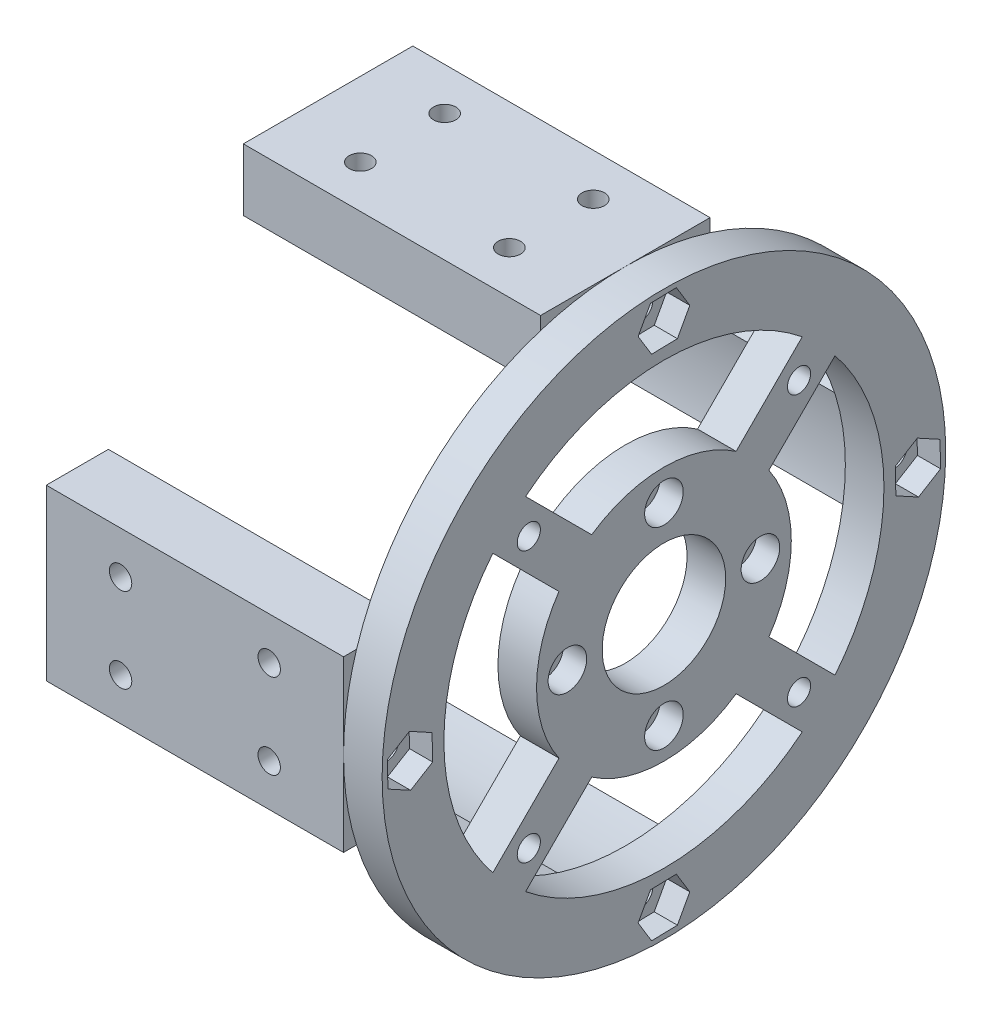
SolidWorks part; units mm, degrees
material "聚脂树脂"
ref_plane "前视基准面" through (0, 0, 0) normal (0, 0, 1) x (1, 0, 0)
ref_plane "上视基准面" through (0, 0, 0) normal (0, 1, 0) x (1, 0, 0)
ref_plane "右视基准面" through (0, 0, 0) normal (1, 0, 0) x (0, 0, -1)
sketch "草图1" plane through (0, 0, 0) normal (1, 0, 0) x (0, 0, -1)
  line L2 (13.5941, 9.3515) -> (22.1619, 17.9193)
  line L3 (9.3515, 13.5941) -> (17.9193, 22.1619)
  line L4 (13.5941, -9.3515) -> (22.1619, -17.9193)
  line L5 (9.3515, -13.5941) -> (17.9193, -22.1619)
  line L6 (-9.3515, -13.5941) -> (-17.9193, -22.1619)
  line L7 (-13.5941, -9.3515) -> (-22.1619, -17.9193)
  line L8 (-13.5941, 9.3515) -> (-22.1619, 17.9193)
  line L9 (-9.3515, 13.5941) -> (-17.9193, 22.1619)
  circle A0 centre (0, 0) radius 36.5
  circle A2 centre (0, 12.5) radius 1.55
  circle A3 centre (12.5, 0) radius 1.55
  circle A4 centre (0, -12.5) radius 1.55
  circle A5 centre (-12.5, 0) radius 1.55
  circle A6 centre (0, 0) radius 8
  arc A7 (17.9193, 22.1619) -> (-17.9193, 22.1619) centre (0, 0) ccw
  arc A8 (9.3515, 13.5941) -> (-9.3515, 13.5941) centre (0, 0) ccw
  arc A9 (-13.5941, 9.3515) -> (-13.5941, -9.3515) centre (0, 0) ccw
  arc A10 (-9.3515, -13.5941) -> (9.3515, -13.5941) centre (0, 0) ccw
  arc A14 (13.5941, -9.3515) -> (13.5941, 9.3515) centre (0, 0) ccw
  arc A15 (-22.1619, 17.9193) -> (-22.1619, -17.9193) centre (0, 0) ccw
  arc A16 (-17.9193, -22.1619) -> (17.9193, -22.1619) centre (0, 0) ccw
  arc A17 (22.1619, -17.9193) -> (22.1619, 17.9193) centre (0, 0) ccw
  point P15 (0, 0)
  point P37 (0, 0)
  dimension "73" = 73
  dimension "D3" = 3.1
  dimension "D5" = 16
  dimension "D6" = 57
  dimension "D7" = 33
  dimension "D4" = 4
  dimension "D11" = 4
extrude "凸台-拉伸1" add sketch "草图1" against normal blind 5
sketch "草图2" plane through (-5, 0, 0) normal (-1, 0, 0) x (0, 0, 1)
  line L0 (0, 30.5) -> (0, 36.5)
  line L1 (5.9179, 29.9204) -> (7.0821, 35.8063)
  line L2 (-7.0821, 35.8063) -> (-5.9179, 29.9204)
  line L3 (29.9025, -6.0076) -> (35.7885, -7.1718)
  line L4 (35.7885, 6.9924) -> (29.9025, 5.8282)
  line L5 (-6.0255, -29.9922) -> (-7.1896, -35.8781)
  line L6 (6.9745, -35.8781) -> (5.8104, -29.9922)
  line L7 (-30.01, 5.9358) -> (-35.896, 7.1)
  line L8 (-35.896, -7.0642) -> (-30.01, -5.9)
  circle A0 centre (0, 0) radius 30.5
  circle A1 centre (0, 0) radius 36.5 construction
  circle A2 centre (0, 0) radius 36.5
  point P12 (6.5, 32.8634)
  point P13 (0, 33.5)
  point P14 (-6.5, 32.8634)
  point P30 (-0.0538, -0.0359)
  dimension "D1" = 61
  dimension "D2" = 6.5
  dimension "D3" = 6.5
  dimension "D4" = 4
sketch "草图3" plane through (0, 0, 0) normal (1, 0, 0) x (0, 0, -1)
  circle A2 centre (2.4306, -32.8101) radius 1.55
  circle A3 centre (35.9279, -71.3329) radius 1.55
  circle A4 centre (-2.5949, -104.8302) radius 1.55
  circle A5 centre (-36.0922, -66.3074) radius 1.55
  circle A6 centre (0, 0) radius 32.9
  point P16 (-0.0822, -68.8201)
  dimension "D1" = 65.8
  dimension "D2" = 3.1
  dimension "D3" = 4
sketch "草图4" plane through (0, 0, 0) normal (1, 0, 0) x (0, 0, -1)
  line L0 (29.904, 6) -> (35.7868, 7.1803)
  line L1 (29.904, -6) -> (35.7868, -7.1803)
  line L2 (6, 29.904) -> (7.1803, 35.7868)
  line L3 (6, -29.904) -> (7.1803, -35.7868)
  line L4 (-6, 29.904) -> (-7.1803, 35.7868)
  line L5 (0, 30.5) -> (0, 36.5)
  line L6 (-6, -29.904) -> (-7.1803, -35.7868)
  line L7 (-29.904, -6) -> (-35.7868, -7.1803)
  line L8 (-29.904, 6) -> (-35.7868, 7.1803)
  circle A0 centre (0, 0) radius 36.5
  circle A1 centre (0, 0) radius 36.5
  circle A2 centre (0, 0) radius 36.5
  circle A3 centre (0, 0) radius 30.5
  point P27 (0, 0)
  dimension "D2" = 61
  dimension "D3" = 6
  dimension "D4" = 4
  dimension "D1" = 0
sketch "草图5" plane through (0, 0, 0) normal (1, 0, 0) x (0, 0, -1)
  line L0 (-0.0065, -0.0065) -> (-0.0065, -32.9065)
  circle A1 centre (-0.0065, -32.9065) radius 1.55
  circle A2 centre (-32.9, 0) radius 1.55
  circle A3 centre (0.0065, 32.8935) radius 1.55
  circle A4 centre (32.9, -0.013) radius 1.55
  point P14 (0, -0.0065)
  dimension "D2" = 3.1
  dimension "D1" = 32.9
  dimension "D3" = 4
extrude "切除-拉伸2" cut sketch "草图5" against normal up to next
sketch "草图7" plane through (0, 0, 0) normal (1, 0, 0) x (0, 0, -1)
  circle A0 centre (0.0001, -32.9065) radius 1.55
  dimension "D1" = 3.1
  dimension "D2" = 32.9
extrude "切除-拉伸3" cut sketch "草图7" against normal up to next
sketch "草图8" plane through (0, 0, 0) normal (1, 0, 0) x (0, 0, -1)
  line L30 (35.8368, -1.6063) -> (35.7573, 1.7389)
  line L31 (3.3517, 32.973) -> (1.6102, 35.8303)
  line L32 (1.6102, 35.8303) -> (-1.735, 35.7508)
  line L33 (-1.735, 35.7508) -> (-3.3387, 32.814)
  line L34 (-3.3387, 32.814) -> (-1.5973, 29.9568)
  line L35 (-1.5973, 29.9568) -> (1.7479, 30.0362)
  line L36 (1.7479, 30.0362) -> (3.3517, 32.973)
  line L43 (35.7573, 1.7389) -> (32.8206, 3.3427)
  line L44 (32.8206, 3.3427) -> (29.9633, 1.6013)
  line L45 (29.9633, 1.6013) -> (30.0428, -1.7439)
  line L46 (30.0428, -1.7439) -> (32.9795, -3.3477)
  line L47 (32.9795, -3.3477) -> (35.8368, -1.6063)
  line L48 (-1.5997, -35.8328) -> (1.7455, -35.7534)
  line L49 (1.7455, -35.7534) -> (3.3492, -32.8166)
  line L50 (3.3492, -32.8166) -> (1.6078, -29.9593)
  line L51 (1.6078, -29.9593) -> (-1.7374, -30.0388)
  line L52 (-1.7374, -30.0388) -> (-3.3411, -32.9756)
  line L53 (-3.3411, -32.9756) -> (-1.5997, -35.8328)
  line L54 (-35.8263, 1.6037) -> (-35.7468, -1.7415)
  line L55 (-35.7468, -1.7415) -> (-32.81, -3.3453)
  line L56 (-32.81, -3.3453) -> (-29.9528, -1.6038)
  line L57 (-29.9528, -1.6038) -> (-30.0322, 1.7414)
  line L58 (-30.0322, 1.7414) -> (-32.969, 3.3451)
  line L59 (-32.969, 3.3451) -> (-35.8263, 1.6037)
  circle A1 centre (0.0065, 32.8935) radius 2.8978 construction
  point P29 (0.0053, -0.0013)
  point P30 (0, 0)
  dimension "D1" = 4
extrude "切除-拉伸4" cut sketch "草图8" against normal blind 3
sketch "草图9" plane through (-5, 0, 0) normal (-1, 0, 0) x (0, 0, 1)
  line L0 (0, 30.5) -> (0, 36.5) construction
  line L1 (0, 0) -> (32.9, 0) construction
  line L2 (0, 0) -> (34.8107, 10.9758) construction
  line L3 (-29.904, -6) -> (-35.7868, -7.1803) construction
  line L4 (-10.9758, 34.8107) -> (-10.9758, 36.5)
  line L5 (-10.9758, 36.5) -> (10.9758, 36.5)
  line L6 (6, -29.904) -> (7.1803, -35.7868) construction
  line L7 (-6, -29.904) -> (-7.1803, -35.7868) construction
  line L8 (-29.904, 6) -> (-35.7868, 7.1803) construction
  line L9 (0, 30.5) -> (0, 36.5)
  line L10 (0, 0) -> (34.8107, -10.9758)
  line L11 (34.8107, -10.9758) -> (29.0884, -9.1715) construction
  line L12 (-29.904, -6) -> (-35.7868, -7.1803)
  line L13 (34.8107, 10.9758) -> (29.0884, 9.1715) construction
  line L14 (10.9758, 36.5) -> (10.9758, 34.8107)
  line L15 (6, -29.904) -> (7.1803, -35.7868)
  line L16 (-6, -29.904) -> (-7.1803, -35.7868)
  line L17 (-29.904, 6) -> (-35.7868, 7.1803)
  line L18 (0, 0) -> (-10.9758, 34.8107) construction
  line L19 (0, 0) -> (10.9758, 34.8107) construction
  line L20 (-10.9758, 34.8107) -> (10.9758, 34.8107) construction
  line L21 (-10.9758, 34.8107) -> (-9.1891, 29.1441) construction
  line L22 (10.9758, 34.8107) -> (9.1715, 29.0884) construction
  line L23 (-10.9758, 34.8107) -> (-10.9758, 28.4567)
  line L24 (10.9758, 34.8107) -> (10.9758, 28.4567)
  line L25 (34.8107, 10.9758) -> (36.5, 10.9758)
  line L26 (36.5, 10.9758) -> (36.5, -10.9758)
  line L27 (36.5, -10.9758) -> (34.8107, -10.9758)
  line L28 (34.8107, -10.9758) -> (28.4567, -10.9758)
  line L29 (34.8107, 10.9758) -> (28.4567, 10.9758)
  line L30 (36.5, 10.9758) -> (28.4567, 10.9758)
  line L31 (36.5, -10.9758) -> (28.4567, -10.9758)
  circle A1 centre (0, 0) radius 30.5
  circle A2 centre (0, 0) radius 30.5
  circle A5 centre (0, 0) radius 36.5
  circle A6 centre (0, 0) radius 36.5
  arc A8 (-9.1891, 29.1441) -> (9.1715, 29.0884) centre (-0.0979, -0.2309) cw
  arc A9 (29.0884, -9.1715) -> (29.0884, 9.1715) centre (0, 0) ccw
  arc A10 (34.8107, -10.9758) -> (34.8107, 10.9758) centre (0, 0) ccw
  dimension "D5" = 35
  dimension "D4" = 35
  dimension "D1" = 0
  dimension "D3" = 0
extrude "凸台-拉伸4" add sketch "草图9" along normal blind 38.5
sketch "草图10" plane through (0, 0, 0) normal (1, 0, 0) x (0, 0, -1)
  line L5 (-17.5, -17.5) -> (17.5, 17.5) construction
  line L6 (-17.5, 17.5) -> (17.5, -17.5) construction
  circle A0 centre (-17.5, 17.5) radius 1.5
  point P0 (0, 0)
  dimension "D2" = 3
  dimension "D1" = 35
extrude "切除-拉伸5" cut sketch "草图10" against normal blind 5
pattern_circular "阵列(圆周)1" count 4 over 360 about axis through (0, 0, 0) along (1, 0, 0) of "切除-拉伸5"
sketch "草图16" plane through (0, 0, 36.5) normal (0, 0, 1) x (1, 0, 0)
  line L0 (-5, -0.0359) -> (-43.5, 0) construction
  line L1 (-43.5, 10.9758) -> (-43.5, -10.9758) construction
  line L2 (-5, 1.5) -> (-43.5, 1.5) construction
  line L3 (-5, 36.5) -> (-5, -36.5) construction
  line L4 (-5, -1.5) -> (-43.5, -1.5) construction
  line L5 (-43.5, 5.4758) -> (-5, 5.4758) construction
  line L6 (-5, 30.5) -> (-5, -30.5) construction
  line L7 (-43.5102, -5.4758) -> (-5.0103, -5.5475) construction
  line L8 (-24.25, 10.9758) -> (-24.25, -10.9758) construction
  line L9 (-43.5, 10.9758) -> (-5, 10.9758) construction
  line L10 (-43.5, -10.9758) -> (-5, -10.9758) construction
  line L11 (-43.5, 10.9758) -> (-43.5, -10.9758)
  line L12 (-33.875, 10.9758) -> (-33.875, -10.9758) construction
  line L13 (-14.625, 10.9758) -> (-14.625, -10.9758) construction
  circle A1 centre (-14.625, 5.4758) radius 1.45
  circle A2 centre (-33.875, -5.4937) radius 1.45
  circle A3 centre (-14.625, -5.5296) radius 1.45
  circle A4 centre (-33.875, 5.4758) radius 1.45
  dimension "D5" = 2.9
  dimension "D6" = 2.9
  dimension "D7" = 2.9
  dimension "D8" = 2.9
  dimension "D1" = 1.5
  dimension "D2" = 1.5
  dimension "D3" = 5.5
  dimension "D4" = 9.625
extrude "切除-拉伸6" cut sketch "草图16" against normal blind 3 contours A4 | A1 | A2 | A3
sketch "草图17" plane through (0, 36.5, 0) normal (0, 1, 0) x (1, 0, 0)
  line L0 (-24.25, 10.9758) -> (-24.25, -10.9758) construction
  line L1 (-43.5, 10.9758) -> (-5, 10.9758) construction
  line L2 (-43.5, -10.9758) -> (-5, -10.9758) construction
  line L3 (-33.875, 10.9758) -> (-33.875, -10.9758) construction
  line L4 (-43.5, 0) -> (-5, 0.0538) construction
  line L5 (-43.5, 5.4758) -> (-5, 5.4758) construction
  line L6 (-43.5, 10.9758) -> (-43.5, -10.9758) construction
  line L7 (-5, 30.5) -> (-5, -30.5) construction
  line L8 (-5, 6.0255) -> (-5, 7.1896) construction
  line L9 (-43.4847, -5.4757) -> (-4.9849, -5.3682) construction
  line L10 (-14.625, 10.9758) -> (-14.625, -10.9758) construction
  circle A0 centre (-33.875, 5.4758) radius 1.45
  circle A1 centre (-14.625, 5.4758) radius 1.45
  circle A2 centre (-33.875, -5.4489) radius 1.45
  circle A3 centre (-14.625, -5.3951) radius 1.45
  dimension "D3" = 2.9
  dimension "D4" = 2.9
  dimension "D5" = 2.9
  dimension "D6" = 2.9
  dimension "D1" = 9.625
  dimension "D2" = 5.5
extrude "切除-拉伸7" cut sketch "草图17" against normal blind 3
sketch "草图18" plane through (0, 0, 0) normal (1, 0, 0) x (0, 0, -1)
  circle A0 centre (0, -12.5) radius 2.5
  circle A1 centre (12.5, 0) radius 2.5
  circle A2 centre (0, 12.5) radius 2.5
  circle A3 centre (-12.5, 0) radius 2.5
extrude "切除-拉伸8" cut sketch "草图18" against normal blind 3
